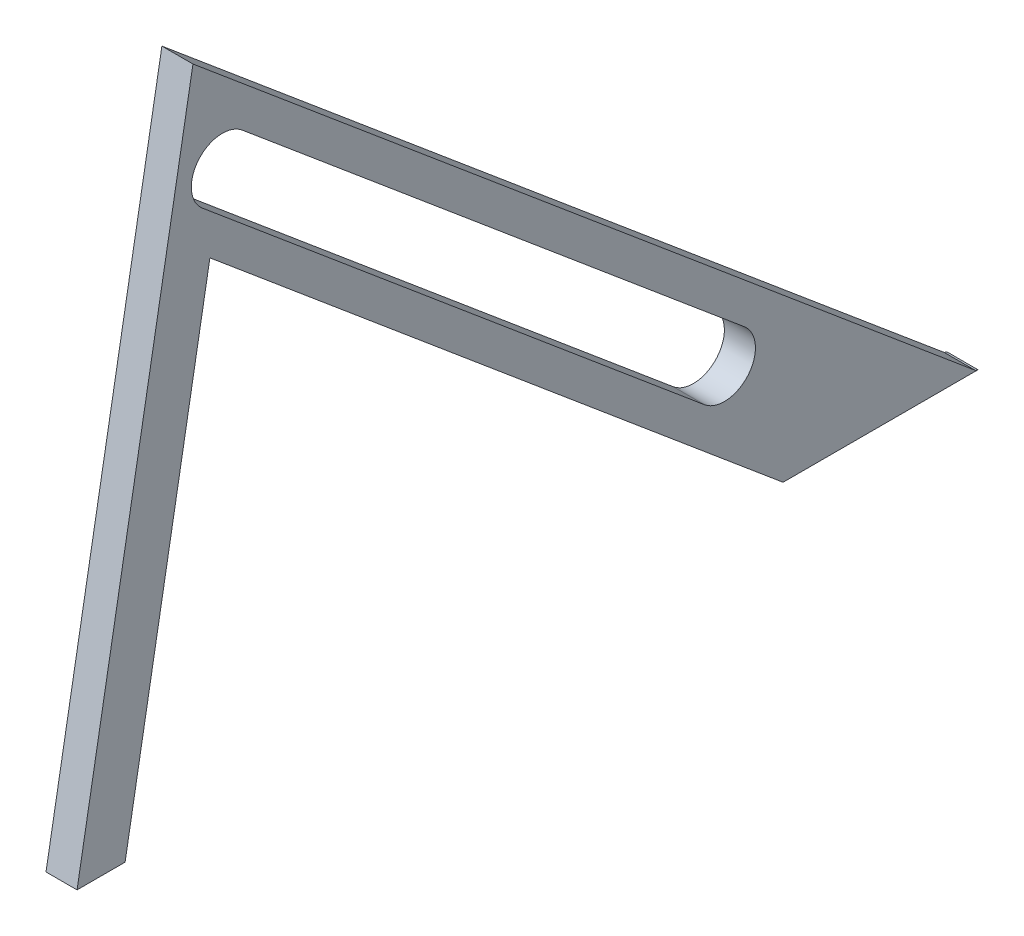
SolidWorks part; units mm, degrees
ref_plane "Front Plane" through (0, 0, 0) normal (0, 0, 1) x (1, 0, 0)
ref_plane "Top Plane" through (0, 0, 0) normal (0, 1, 0) x (1, 0, 0)
ref_plane "Right Plane" through (0, 0, 0) normal (1, 0, 0) x (0, 0, -1)
sketch "Sketch1" plane through (0, 0, 0) normal (1, 0, 0) x (0, 0, -1)
  line L0 (-444.5, 0) -> (444.5, 0) construction
  line L1 (-444.5, 0) -> (-397.0929, 268.859) construction
  line L2 (-397.0929, 268.859) -> (-444.5, 0)
  line L3 (-397.0929, 268.859) -> (-77.079, 0.3354)
  line L4 (-397.0929, 268.859) -> (-397.0929, 0) construction
  line L9 (-77.079, 0.3354) -> (-75.9791, 0)
  line L10 (-237.0859, 134.5972) -> (-286.7402, 75.4216) construction
  line L16 (-286.7402, 75.4216) -> (-413.7726, 182.0144) construction
  line L17 (-286.7402, 75.4216) -> (-96.4268, -84.2704) construction
  line L18 (-397.0929, 0) -> (-397.0929, -231.14) construction
  line L19 (-245.2493, 124.8685) -> (-320.9886, 188.4213) construction
  line L20 (-261.5762, 105.4109) -> (-354.6717, 183.5274) construction
  line L21 (-269.7396, 95.6822) -> (-390.1563, 196.7238)
  line L22 (-269.7396, 95.6822) -> (-155.71, 0)
  line L23 (-420.7965, 134.4295) -> (-382.6698, 127.7067) construction
  line L24 (-401.7331, 131.0681) -> (-424.844, 0) construction
  line L25 (-401.7331, 131.0681) -> (-390.1563, 196.7238) construction
  line L26 (-390.1563, 196.7238) -> (-424.844, 0)
  line L28 (-328.6917, 194.8849) -> (-345.0185, 175.4274) construction
  line L29 (-336.8551, 185.1562) -> (-385.0633, 225.6076) construction
  line L30 (-336.8551, 185.1562) -> (-179.7174, 53.3019) construction
  line L31 (-385.0633, 225.6076) -> (-179.7174, 53.3019) construction
  line L32 (-376.8999, 235.3364) -> (-171.554, 63.0307)
  line L33 (-393.2267, 215.8788) -> (-187.8808, 43.5732)
  line L34 (-444.5, 0) -> (-424.844, 0)
  line L35 (-155.71, 0) -> (-75.9791, 0)
  line L36 (-387.6098, 211.1657) -> (-379.9703, 254.4914) construction
  arc A2 (-376.8999, 235.3364) -> (-393.2267, 215.8788) centre (-385.0633, 225.6076) ccw
  arc A3 (-187.8808, 43.5732) -> (-171.554, 63.0307) centre (-179.7174, 53.3019) ccw
  point P4 (0, 0)
  point P32 (-282.3903, 139.4548)
  dimension "D1" = 889
  dimension "D7" = 12.7
  dimension "D2" = 231.14
  dimension "D3" = 499.999
  dimension "D4" = 25.4
  dimension "D5" = 12.7
  dimension "D6" = 12.7
  dimension "D8" = 19.656
  dimension "D9" = 268.0601
  dimension "D10" = 40
  dimension "D11" = 80
extrude "Boss-Extrude1" add sketch "Sketch1" along normal blind 12.7
